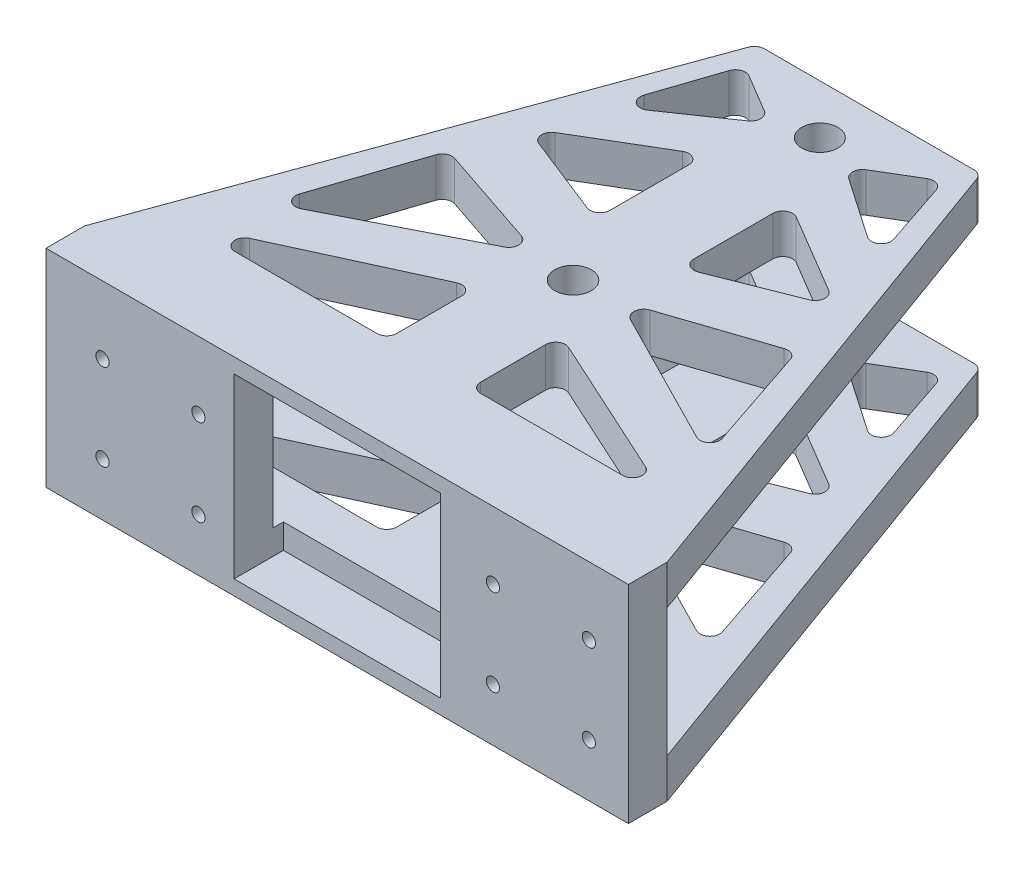
SolidWorks part; units mm, degrees
ref_plane "Front Plane" through (0, 0, 0) normal (0, 0, 1) x (1, 0, 0)
ref_plane "Top Plane" through (0, 0, 0) normal (0, 1, 0) x (1, 0, 0)
ref_plane "Right Plane" through (0, 0, 0) normal (1, 0, 0) x (0, 0, -1)
sketch "Sketch1" plane through (0, 0, 0) normal (0, 0, 1) x (1, 0, 0)
  line L1 (-75, -26.67) -> (75, -26.67)
  line L2 (-75, -26.67) -> (-75, 26.67)
  line L3 (-75, 26.67) -> (75, 26.67)
  line L4 (75, -26.67) -> (75, 26.67)
  line L5 (-75, -26.67) -> (75, 26.67) construction
  line L6 (-75, 26.67) -> (75, -26.67) construction
  point P0 (0, 0)
  dimension "D1" = 150
  dimension "D2" = 53.34
extrude "Boss-Extrude1" add sketch "Sketch1" along normal blind 10
sketch "Sketch4" plane through (0, 0, 0) normal (0, 0, -1) x (-1, 0, 0)
  line L0 (0, 0) -> (0, 26.67) construction
  line L1 (-75, 26.67) -> (75, 26.67) construction
  line L2 (75, 26.67) -> (75, -26.67) construction
  line L3 (-75, 26.67) -> (75, 26.67)
  line L4 (-75, 26.67) -> (-75, 16.51)
  line L5 (-75, 16.51) -> (75, 16.51)
  line L6 (75, 26.67) -> (75, 16.51)
  line L7 (0, 0) -> (0, -26.67) construction
  line L8 (75, -26.67) -> (-75, -26.67) construction
  line L10 (-75, -26.67) -> (75, -26.67)
  line L11 (-75, -26.67) -> (-75, -16.51)
  line L12 (-75, -16.51) -> (75, -16.51)
  line L13 (75, -26.67) -> (75, -16.51)
  dimension "D1" = 10.16
  dimension "D2" = 10.16
extrude "Boss-Extrude3" add sketch "Sketch4" along normal blind 127
sketch "Sketch6" plane through (0, 26.67, 0) normal (0, 1, 0) x (1, 0, 0)
  line L0 (0, -10) -> (0, 0) construction
  line L1 (75, -10) -> (-75, -10) construction
  line L2 (0, 0) -> (-75, 0) construction
  line L3 (-75, -10) -> (-75, 127) construction
  line L4 (-75, 0) -> (75, 0) construction
  line L5 (75, -10) -> (75, 127) construction
  line L6 (75, 0) -> (28.7758, 127) construction
  line L7 (-75, 127) -> (75, 127) construction
  line L8 (28.7758, 127) -> (75, 127) construction
  line L9 (75, 127) -> (75, 0) construction
  line L10 (28.7758, 127) -> (75, 0)
  line L11 (75, 0) -> (75, 127)
  line L12 (75, 127) -> (28.7758, 127)
  line L13 (-75, 0) -> (-75, 127)
  line L14 (-75, 127) -> (-28.7758, 127)
  line L15 (-28.7758, 127) -> (-75, 0)
  dimension "D1" = 70
  dimension "D2" = 127
  dimension "D3" = 70
extrude "Cut-Extrude1" cut sketch "Sketch6" against normal blind 83.82
fillet "Fillet1" radius 2.54 4 edges at (28.7758, -21.59, -127) (-28.7758, -21.59, -127) (28.7758, 21.59, -127) (-28.7758, 21.59, -127)
sketch "Sketch7" plane through (0, 26.67, 0) normal (0, 1, 0) x (1, 0, 0)
  line L0 (-26.9973, 127) -> (26.9973, 127) construction
  line L2 (0, 127) -> (0, 101.6) construction
  line L3 (-26.9973, 127) -> (-26.9973, 101.6) construction
  line L4 (-26.9973, 101.6) -> (26.9973, 101.6) construction
  line L5 (26.9973, 101.6) -> (26.9973, 127) construction
  circle A0 centre (0, 114.3) radius 4.6498
  point P3 (0, 127)
  dimension "D1" = 12.7
extrude "Cut-Extrude2" cut sketch "Sketch7" against normal blind 83.82
sketch "Sketch8" plane through (0, 0, 10) normal (0, 0, 1) x (1, 0, 0)
  line L1 (-26.5528, -22.86) -> (26.5528, -22.86)
  line L2 (-26.5528, -22.86) -> (-26.5528, 22.86)
  line L3 (-26.5528, 22.86) -> (26.5528, 22.86)
  line L4 (26.5528, -22.86) -> (26.5528, 22.86)
  line L5 (-26.5528, -22.86) -> (26.5528, 22.86) construction
  line L6 (-26.5528, 22.86) -> (26.5528, -22.86) construction
  point P0 (0, 0)
extrude "Cut-Extrude3" cut sketch "Sketch8" against normal blind 12.7
sketch "Sketch9" plane through (0, 26.67, 0) normal (0, 1, 0) x (1, 0, 0)
  line L46 (-34.5864, 93.9691) -> (-9.6846, 111.0821)
  line L47 (-9.6846, 111.0821) -> (-25.6407, 120.6076)
  line L48 (-25.6407, 120.6076) -> (-34.5864, 93.9691)
  line L49 (-39.7043, 78.7291) -> (-10.828, 95.8421)
  line L50 (-39.7043, 78.7291) -> (-10.828, 67.3132)
  line L51 (-10.828, 67.3132) -> (-10.828, 95.8421)
  line L52 (-10.828, 52.0732) -> (-44.8222, 63.4891)
  line L54 (-56.4608, 28.8322) -> (-10.828, 52.0732)
  line L55 (-10.828, 36.8332) -> (-61.5787, 13.5922)
  line L56 (-61.5787, 13.5922) -> (-10.828, 13.5922)
  line L57 (-10.828, 13.5922) -> (-10.828, 36.8332)
  line L58 (-44.8222, 63.4891) -> (-56.4608, 28.8322)
  dimension "D2" = 15.24
  dimension "D3" = 15.24
  dimension "D4" = 15.24
  dimension "D5" = 15.24
  dimension "D6" = 0
  dimension "D7" = 0
  dimension "D8" = 0
  dimension "D9" = 15.24
  dimension "D10" = 15.24
extrude "Cut-Extrude4" cut sketch "Sketch9" against normal through all
mirror "Mirror1" about plane through (0, 0, 0) normal (1, 0, 0) of "Cut-Extrude4"
fillet "Fillet2" radius 2.54 26 edges at (61.5787, 21.59, -13.5922) (10.828, 21.59, -13.5922) (10.828, 21.59, -36.8332) (25.6407, 21.59, -120.6076) (34.5864, 21.59, -93.9691) (9.6846, 21.59, -111.0821) (56.4608, 21.59, -28.8322) (10.828, 21.59, -52.0732) (44.8222, 21.59, -63.4891) (39.7043, 21.59, -78.7291) (10.828, 21.59, -95.8421) (10.828, 21.59, -67.3132) (-9.6846, 21.59, -111.0821) (-10.828, 21.59, -95.8421) (-10.828, 21.59, -67.3132) (-39.7043, 21.59, -78.7291) (-34.5864, 21.59, -93.9691) (-25.6407, 21.59, -120.6076) (-44.8222, 21.59, -63.4891) (-56.4608, 21.59, -28.8322) (-10.828, 21.59, -52.0732) (-61.5787, 21.59, -13.5922) (-10.828, 21.59, -36.8332) (-10.828, 21.59, -13.5922) (-39.7043, -21.59, -78.7291) (9.6846, -21.59, -111.0821)
fillet "Fillet3" radius 2.54 22 edges at (10.828, -21.59, -13.5922) (10.828, -21.59, -36.8332) (61.5787, -21.59, -13.5922) (56.4608, -21.59, -28.8322) (44.8222, -21.59, -63.4891) (10.828, -21.59, -52.0732) (10.828, -21.59, -67.3132) (10.828, -21.59, -95.8421) (39.7043, -21.59, -78.7291) (34.5864, -21.59, -93.9691) (25.6407, -21.59, -120.6076) (-34.5864, -21.59, -93.9691) (-25.6407, -21.59, -120.6076) (-9.6846, -21.59, -111.0821) (-10.828, -21.59, -67.3132) (-10.828, -21.59, -95.8421) (-56.4608, -21.59, -28.8322) (-10.828, -21.59, -52.0732) (-44.8222, -21.59, -63.4891) (-61.5787, -21.59, -13.5922) (-10.828, -21.59, -36.8332) (-10.828, -21.59, -13.5922)
sketch "Sketch10" plane through (0, 0, 10) normal (0, 0, 1) x (1, 0, 0)
  circle A0 centre (40.1138, 9.2393) radius 1.7
  circle A1 centre (64.8278, 9.2393) radius 1.7
  circle A2 centre (64.8278, -13.0493) radius 1.7
  circle A3 centre (40.1138, -13.0493) radius 1.7
  circle A4 centre (-60.4502, 9.2393) radius 1.7
  circle A5 centre (-35.7362, 9.2393) radius 1.7
  circle A6 centre (-35.7362, -13.0493) radius 1.7
  circle A7 centre (-60.4502, -13.0493) radius 1.7
extrude "Cut-Extrude5" cut sketch "Sketch10" against normal up to next
sketch "Sketch11" plane through (0, 26.67, 0) normal (0, 1, 0) x (1, 0, 0)
  circle A0 centre (0, 50.7398) radius 4.699
  dimension "D1" = 9.398
extrude "Cut-Extrude6" cut sketch "Sketch11" against normal through all
